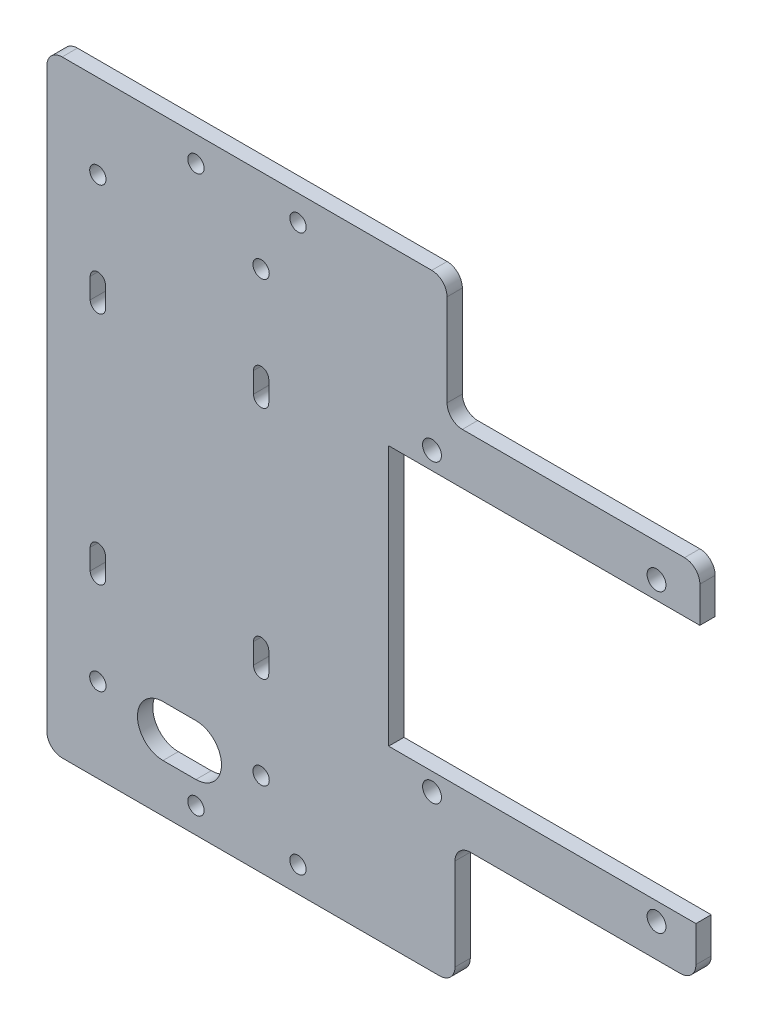
SolidWorks part; units mm, degrees
ref_plane "前视基准面" through (0, 0, 0) normal (0, 0, 1) x (1, 0, 0)
ref_plane "上视基准面" through (0, 0, 0) normal (0, 1, 0) x (1, 0, 0)
ref_plane "右视基准面" through (0, 0, 0) normal (1, 0, 0) x (0, 0, -1)
other "Configuration Table"
sketch "草图1" plane through (0, 0, 0) normal (0, 0, 1) x (1, 0, 0)
  line L0 (65.7597, 31.4573) -> (53.5352, 31.4573)
  line L1 (15.7597, 60.4573) -> (35.7597, 60.4573) construction
  line L2 (15.7597, 60.4573) -> (15.7597, -48.5427) construction
  line L3 (15.7597, -48.5427) -> (35.7597, -48.5427) construction
  line L4 (35.7597, 60.4573) -> (35.7597, -48.5427) construction
  line L5 (-13.4648, 65.4573) -> (64.9841, 65.4573)
  line L6 (-13.4648, 65.4573) -> (-13.4648, -53.5427)
  line L7 (-13.4648, -53.5427) -> (66.5352, -53.5427)
  line L8 (64.9841, 65.4573) -> (64.9841, 41.4573)
  line L9 (-3.4648, 48.9573) -> (28.5352, 48.9573) construction
  line L10 (-3.4648, 48.9573) -> (-3.4648, -37.0427) construction
  line L11 (-3.4648, -37.0427) -> (28.5352, -37.0427) construction
  line L12 (28.5352, 48.9573) -> (28.5352, -37.0427) construction
  line L25 (62.0352, 34.9573) -> (106.0352, 34.9573) construction
  line L26 (62.0352, 34.9573) -> (62.0352, -23.0427) construction
  line L27 (62.0352, -23.0427) -> (106.0352, -23.0427) construction
  line L28 (106.0352, 34.9573) -> (106.0352, -23.0427) construction
  line L29 (53.5352, 31.4573) -> (114.5352, 31.4573) construction
  line L30 (53.5352, 31.4573) -> (53.5352, -19.5427) construction
  line L31 (53.5352, -19.5427) -> (114.5352, -19.5427) construction
  line L32 (114.5352, 31.4573) -> (114.5352, -19.5427) construction
  line L33 (53.5352, 31.4573) -> (53.5352, -19.5427)
  line L34 (53.5352, -19.5427) -> (64.9841, -19.5427)
  line L37 (114.5352, 31.4573) -> (65.7597, 31.4573)
  line L38 (114.5352, 31.4573) -> (114.5352, 41.4573)
  line L39 (114.5352, 41.4573) -> (64.9841, 41.4573)
  line L41 (64.9841, -19.5427) -> (113.7597, -19.5427)
  line L43 (66.5352, -29.5427) -> (113.7597, -29.5427)
  line L44 (113.7597, -19.5427) -> (113.7597, -29.5427)
  line L45 (66.5352, -29.5427) -> (66.5352, -53.5427)
  line L46 (-3.4648, -37.0427) -> (-3.4648, -56.7871) construction
  line L47 (0.5352, 34.9573) -> (24.5352, 34.9573) construction
  line L48 (0.5352, 34.9573) -> (0.5352, -23.0427) construction
  line L49 (0.5352, -23.0427) -> (24.5352, -23.0427) construction
  line L50 (24.5352, 34.9573) -> (24.5352, -23.0427) construction
  line L51 (9.3027, -39.0925) -> (15.7597, -39.0925) construction
  line L52 (9.3027, -34.0925) -> (15.7597, -34.0925)
  line L53 (9.3027, -44.0925) -> (15.7597, -44.0925)
  line L54 (-3.4648, 30.9573) -> (-3.4648, 26.9573) construction
  line L55 (-1.9648, 30.9573) -> (-1.9648, 26.9573)
  line L56 (-4.9648, 30.9573) -> (-4.9648, 26.9573)
  line L57 (-3.4648, -15.0427) -> (-3.4648, -19.0427) construction
  line L58 (-1.9648, -15.0427) -> (-1.9648, -19.0427)
  line L59 (-4.9648, -15.0427) -> (-4.9648, -19.0427)
  line L60 (12.5352, 34.9573) -> (12.5352, -23.0427) construction
  line L61 (28.5352, -15.0427) -> (28.5352, -19.0427) construction
  line L62 (27.0352, -15.0427) -> (27.0352, -19.0427)
  line L63 (30.0352, -15.0427) -> (30.0352, -19.0427)
  line L64 (28.5352, 30.9573) -> (28.5352, 26.9573) construction
  line L65 (27.0352, 30.9573) -> (27.0352, 26.9573)
  line L66 (30.0352, 30.9573) -> (30.0352, 26.9573)
  circle A0 centre (15.7597, 60.4573) radius 1.6
  circle A1 centre (35.7597, 60.4573) radius 1.6
  circle A2 centre (15.7597, -48.5427) radius 1.6
  circle A3 centre (35.7597, -48.5427) radius 1.6
  circle A4 centre (-3.4648, 48.9573) radius 1.6
  circle A5 centre (28.5352, 48.9573) radius 1.6
  circle A6 centre (-3.4648, -37.0427) radius 1.6
  circle A7 centre (28.5352, -37.0427) radius 1.6
  circle A12 centre (62.0352, -23.0427) radius 1.85
  circle A13 centre (106.0352, -23.0427) radius 1.85
  circle A14 centre (62.0352, 34.9573) radius 1.85
  circle A15 centre (106.0352, 34.9573) radius 1.85
  arc A16 (9.3027, -34.0925) -> (9.3027, -44.0925) centre (9.3027, -39.0925) ccw
  arc A17 (15.7597, -44.0925) -> (15.7597, -34.0925) centre (15.7597, -39.0925) ccw
  arc A18 (-1.9648, 30.9573) -> (-4.9648, 30.9573) centre (-3.4648, 30.9573) ccw
  arc A19 (-4.9648, 26.9573) -> (-1.9648, 26.9573) centre (-3.4648, 26.9573) ccw
  arc A20 (-1.9648, -15.0427) -> (-4.9648, -15.0427) centre (-3.4648, -15.0427) ccw
  arc A21 (-4.9648, -19.0427) -> (-1.9648, -19.0427) centre (-3.4648, -19.0427) ccw
  arc A22 (27.0352, -15.0427) -> (30.0352, -15.0427) centre (28.5352, -15.0427) cw
  arc A23 (30.0352, -19.0427) -> (27.0352, -19.0427) centre (28.5352, -19.0427) cw
  arc A24 (27.0352, 30.9573) -> (30.0352, 30.9573) centre (28.5352, 30.9573) cw
  arc A25 (30.0352, 26.9573) -> (27.0352, 26.9573) centre (28.5352, 26.9573) cw
  point P12 (25.7597, 60.4573)
  point P13 (25.7597, 65.4573)
  point P14 (-13.4648, 5.9573)
  point P15 (15.7597, 5.9573)
  point P20 (28.5352, 5.9573)
  point P29 (0.5352, 5.9573)
  point P33 (12.5312, -39.0925)
  point P38 (12.5352, 34.9573)
  point P39 (12.5352, 48.9573)
  point P41 (35.7597, 5.9573)
  point P43 (-3.4648, 28.9573)
  point P51 (84.0352, 34.9573)
  point P52 (84.0352, 31.4573)
  point P61 (53.5352, 5.9573)
  point P62 (62.0352, 5.9573)
  point P71 (-3.4648, -17.0427)
  point P80 (28.5352, -17.0427)
  point P89 (28.5352, 28.9573)
  point P94 (12.5312, -39.0925)
  point P95 (-3.7161, 35.6502)
  point P96 (-3.4648, 29.8709)
  dimension "D3" = 3.2
  dimension "D9" = 3.2
  dimension "D15" = 10
  dimension "D19" = 3.7
  dimension "D13" = 20
  dimension "D1" = 109
  dimension "D2" = 20
  dimension "D4" = 5
  dimension "D5" = 5
  dimension "D6" = 80
  dimension "D7" = 86
  dimension "D8" = 32
  dimension "D10" = 10
  dimension "D11" = 24
  dimension "D12" = 58
  dimension "D14" = 20
  dimension "D16" = 10
  dimension "D17" = 44
  dimension "D18" = 58
  dimension "D20" = 61
  dimension "D21" = 51
  dimension "D22" = 25
extrude "凸台-拉伸1" add sketch "草图1" along normal blind 3
fillet "圆角1" radius 3 8 edges at (64.9841, 65.4573, 1.5) (64.9841, 41.4573, 1.5) (114.5352, 41.4573, 1.5) (113.7597, -29.5427, 1.5) (66.5352, -29.5427, 1.5) (66.5352, -53.5427, 1.5) (-13.4648, -53.5427, 1.5) (-13.4648, 65.4573, 1.5)
